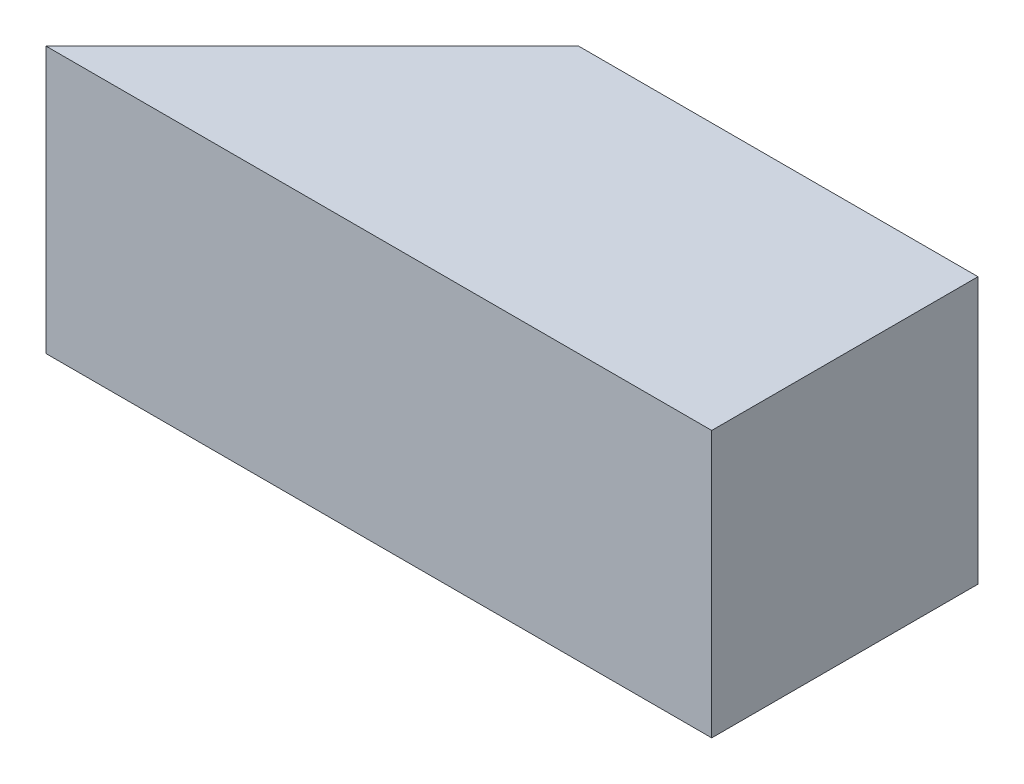
SolidWorks part; units mm, degrees
ref_plane "Front" through (0, 0, 0) normal (0, 0, 1) x (1, 0, 0)
ref_plane "Top" through (0, 0, 0) normal (0, 1, 0) x (1, 0, 0)
ref_plane "Right" through (0, 0, 0) normal (1, 0, 0) x (0, 0, -1)
sketch "Эскиз1" plane through (0, 0, 0) normal (0, 1, 0) x (1, 0, 0)
  line L1 (-241.6915, -177.7121) -> (-181.6915, -177.7121)
  line L3 (-281.6915, -217.7121) -> (-181.6915, -217.7121)
  line L5 (-281.6915, -217.7121) -> (-241.6915, -177.7121)
  line L6 (-181.6915, -177.7121) -> (-181.6915, -217.7121)
  dimension "D1" = 40
  dimension "D2" = 100
  dimension "D4" = 45
extrude "Бобышка-Вытянуть1" add sketch "Эскиз1" along normal blind 40
